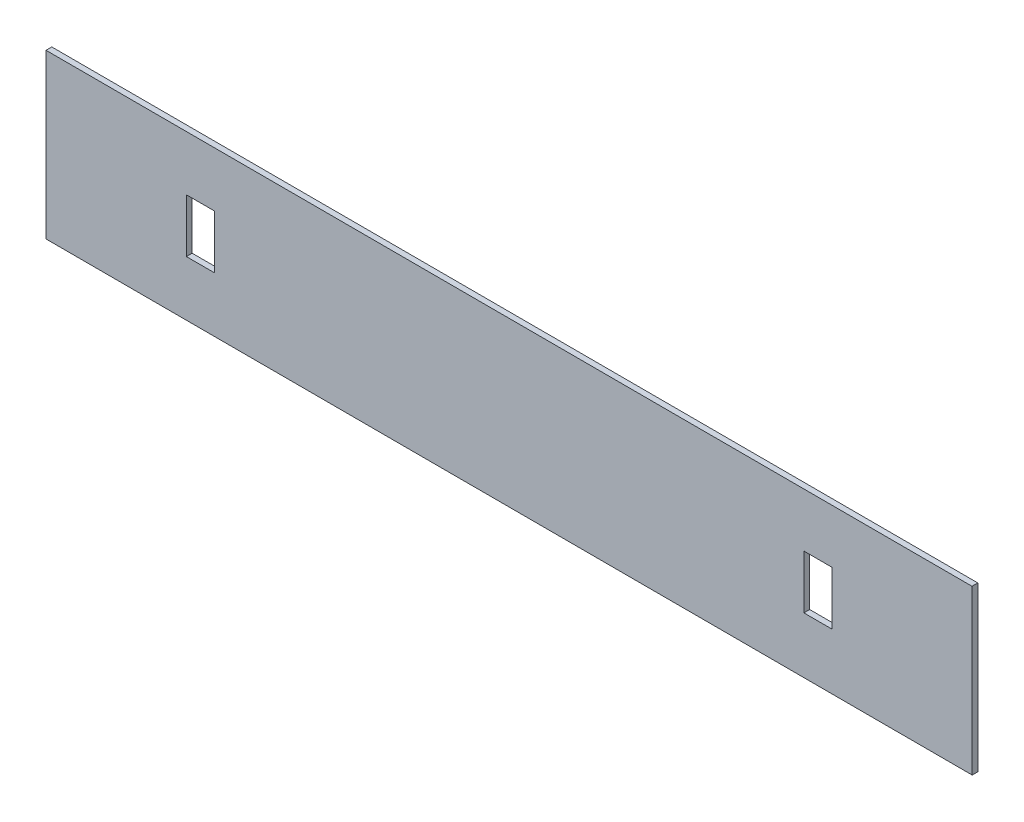
SolidWorks part; units mm, degrees
ref_plane "Front Plane" through (0, 0, 0) normal (0, 0, 1) x (1, 0, 0)
ref_plane "Top Plane" through (0, 0, 0) normal (0, 1, 0) x (1, 0, 0)
ref_plane "Right Plane" through (0, 0, 0) normal (1, 0, 0) x (0, 0, -1)
sketch "Sketch1" plane through (0, 0, 0) normal (0, 0, 1) x (1, 0, 0)
  line L1894 (83.1689, 1031.1917) -> (97.6888, 1031.1917)
  line L1895 (97.6888, 1031.1917) -> (97.6888, 1003.4942)
  line L1896 (97.6888, 1003.4942) -> (83.1689, 1003.4942)
  line L1897 (83.1689, 1003.4942) -> (83.1689, 1031.1917)
  line L1898 (402.676, 1031.3015) -> (417.1959, 1031.2832)
  line L1899 (417.1959, 1031.2832) -> (417.1609, 1003.5857)
  line L1900 (417.1609, 1003.5857) -> (402.641, 1003.604)
  line L1901 (402.641, 1003.604) -> (402.676, 1031.3015)
  line L1902 (10.6729, 975.0731) -> (10.5662, 1059.6178)
  line L1903 (10.5662, 1059.6178) -> (489.6084, 1059.0067)
  line L1904 (489.6084, 1059.0067) -> (489.7151, 974.4619)
  line L1905 (489.7151, 974.4619) -> (10.6729, 975.0731)
  dimension "D1" = 84.5448
  dimension "D2" = 479.0426
  dimension "D3" = 14.5199
  dimension "D4" = 27.6975
  dimension "D5" = 72.5668
  dimension "D6" = 72.4475
  dimension "D7" = 14.5199
extrude "Boss-Extrude1" add sketch "Sketch1" along normal blind 3
